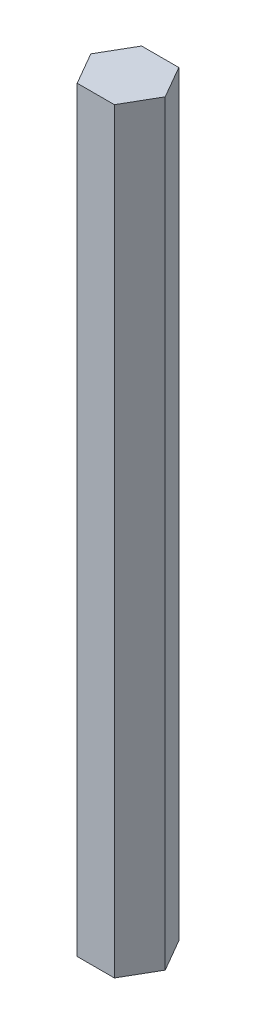
SolidWorks part; units mm, degrees
ref_plane "Front Plane" through (0, 0, 0) normal (0, 0, 1) x (1, 0, 0)
ref_plane "Top Plane" through (0, 0, 0) normal (0, 1, 0) x (1, 0, 0)
ref_plane "Right Plane" through (0, 0, 0) normal (1, 0, 0) x (0, 0, -1)
sketch "Sketch1" plane through (0, 0, 0) normal (0, 1, 0) x (1, 0, 0)
  line L1 (3, 0) -> (1.5, 2.5981)
  line L2 (1.5, 2.5981) -> (-1.5, 2.5981)
  line L3 (-1.5, 2.5981) -> (-3, 0)
  line L4 (-3, 0) -> (-1.5, -2.5981)
  line L5 (-1.5, -2.5981) -> (1.5, -2.5981)
  line L6 (1.5, -2.5981) -> (3, 0)
  circle A0 centre (0, 0) radius 2.5981 construction
  dimension "D1" = 3
extrude "Boss-Extrude1" add sketch "Sketch1" along normal blind 61
sketch "Sketch3" plane through (0, 0, 0) normal (0, -1, 0) x (1, 0, 0)
  circle A0 centre (0, 0) radius 1.6
  dimension "D1" = 3.2
extrude "Cut-Extrude1" cut sketch "Sketch3" against normal blind 5
